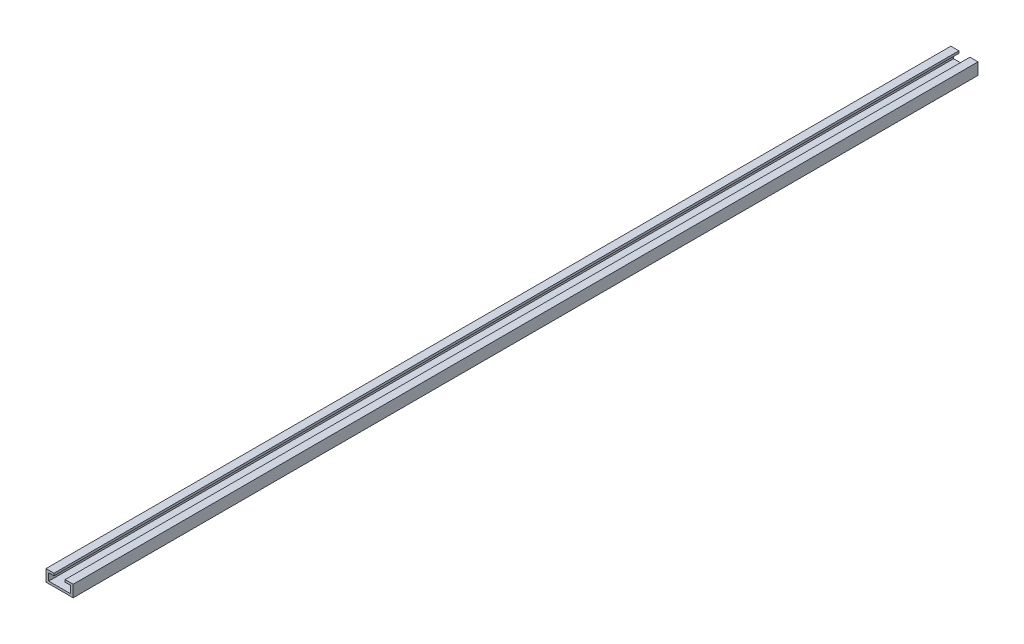
SolidWorks part; units mm, degrees
ref_plane "Front Plane" through (0, 0, 0) normal (0, 0, 1) x (1, 0, 0)
ref_plane "Top Plane" through (0, 0, 0) normal (0, 1, 0) x (1, 0, 0)
ref_plane "Right Plane" through (0, 0, 0) normal (1, 0, 0) x (0, 0, -1)
sketch "Sketch1" plane through (0, 0, 0) normal (0, 0, 1) x (1, 0, 0)
  line L0 (-15, 0) -> (15, 0)
  line L1 (-12, 2.5) -> (12, 2.5)
  line L2 (12, 2.5) -> (12, 10.5283)
  line L3 (12, 13.0283) -> (15, 13.0283)
  line L4 (15, 13.0283) -> (15, 0)
  line L5 (12, 10.5283) -> (6.1, 10.5283)
  line L6 (6.1, 10.5283) -> (6.1, 13.0283)
  line L8 (6.1, 13.0283) -> (12, 13.0283)
  line L9 (-15, 13.0283) -> (-15, 0)
  line L10 (-12, 2.5) -> (-12, 10.5283)
  line L11 (-12, 10.5283) -> (-6.1, 10.5283)
  line L12 (-12, 13.0283) -> (-15, 13.0283)
  line L13 (-6.1, 13.0283) -> (-12, 13.0283)
  line L14 (-6.1, 10.5283) -> (-6.1, 13.0283)
  dimension "D1" = 24
  dimension "D2" = 10.5283
  dimension "D3" = 3
  dimension "D4" = 13.0283
  dimension "D6" = 2.5
extrude "Boss-Extrude1" add sketch "Sketch1" along normal blind 1000
